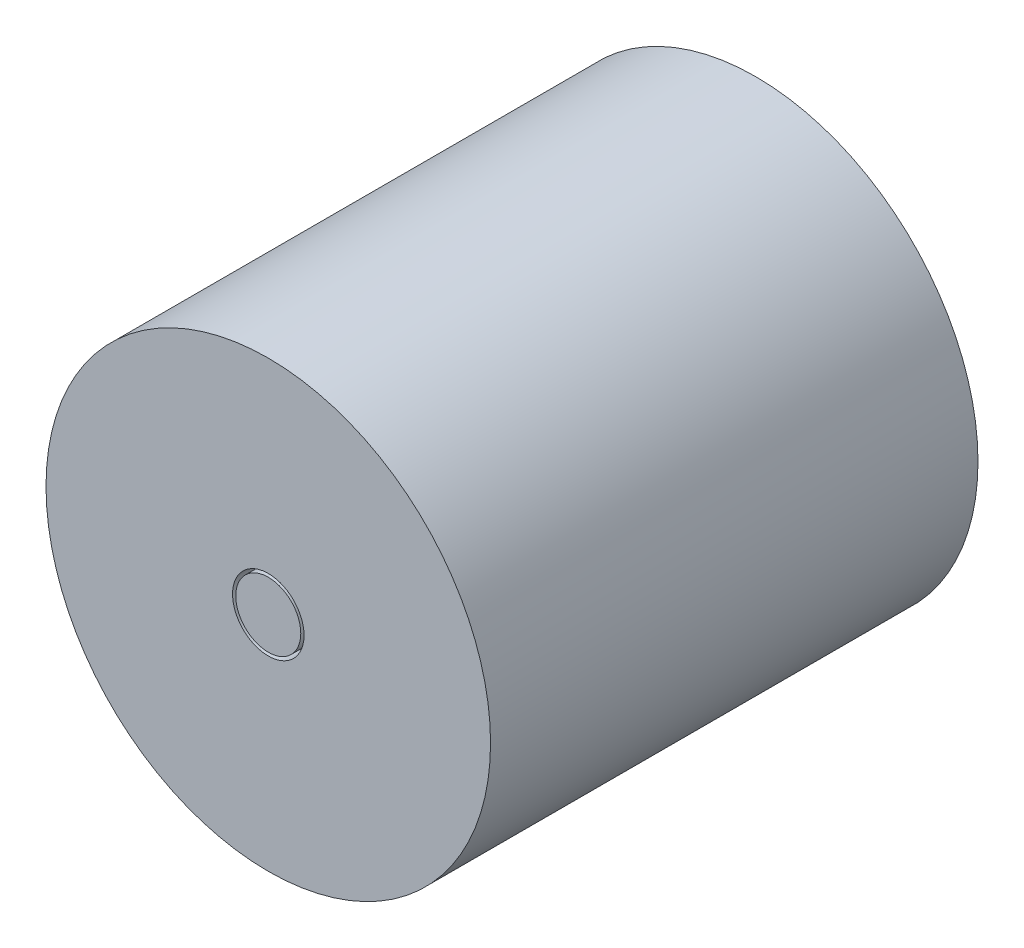
SolidWorks part; units mm, degrees
ref_plane "前基準面" through (0, 0, 0) normal (0, 0, 1) x (1, 0, 0)
ref_plane "上基準面" through (0, 0, 0) normal (0, 1, 0) x (1, 0, 0)
ref_plane "右基準面" through (0, 0, 0) normal (1, 0, 0) x (0, 0, -1)
sketch "草圖1" plane through (0, 0, 0) normal (0, 0, 1) x (1, 0, 0)
  circle A0 centre (0, 0) radius 0.01
extrude "填料-伸長1" add sketch "草圖1" along normal blind 0.15
sketch "草圖2" plane through (0, 0, 0.15) normal (0, 0, 1) x (1, 0, 0)
  circle A0 centre (0, 0) radius 0.0684
  circle A1 centre (0, 0) radius 0.011
extrude "填料-伸長5" add sketch "草圖2" against normal blind 0.15 separate body contours A1 | A0
